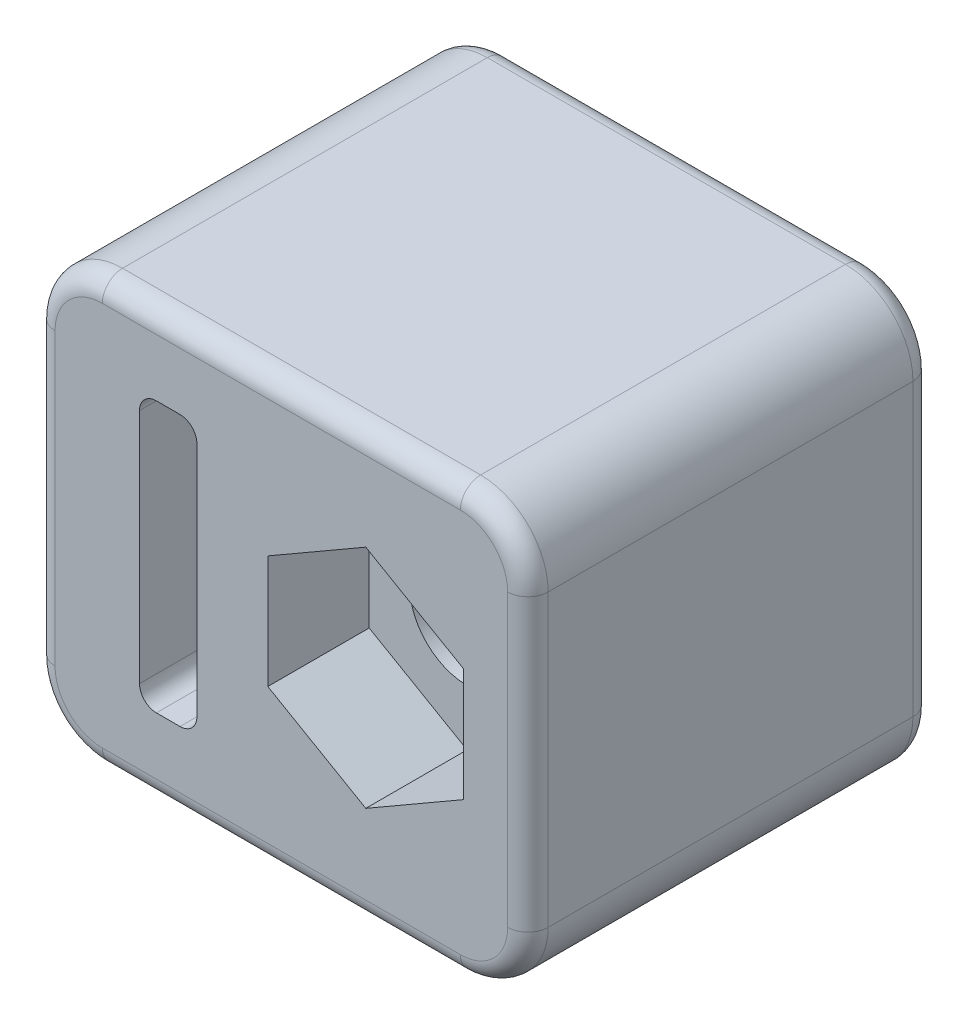
SolidWorks part; units mm, degrees
ref_plane "Front Plane" through (0, 0, 0) normal (0, 0, 1) x (1, 0, 0)
ref_plane "Top Plane" through (0, 0, 0) normal (0, 1, 0) x (1, 0, 0)
ref_plane "Right Plane" through (0, 0, 0) normal (1, 0, 0) x (0, 0, -1)
sketch "Sketch1" plane through (0, 0, 0) normal (0, 0, 1) x (1, 0, 0)
  line L8 (3.1, 9.8) -> (3.1, 2.8)
  line L9 (3.6, 2.3) -> (4.3, 2.3)
  line L10 (4.8, 2.8) -> (4.8, 9.8)
  line L15 (3.6, 10.3) -> (4.3, 10.3)
  line L18 (2, 0) -> (12.6, 0)
  line L19 (0, 2) -> (0, 10.6)
  line L20 (2, 12.6) -> (12.6, 12.6)
  line L21 (14.6, 2) -> (14.6, 10.6)
  arc A13 (3.6, 10.3) -> (3.1, 9.8) centre (3.6, 9.8) ccw
  arc A14 (4.3, 10.3) -> (4.8, 9.8) centre (4.3, 9.8) cw
  arc A15 (3.1, 2.8) -> (3.6, 2.3) centre (3.6, 2.8) ccw
  arc A16 (4.8, 2.8) -> (4.3, 2.3) centre (4.3, 2.8) cw
  circle A17 centre (9.8, 6.3) radius 1.7
  arc A18 (12.6, 12.6) -> (14.6, 10.6) centre (12.6, 10.6) cw
  arc A19 (12.6, 0) -> (14.6, 2) centre (12.6, 2) ccw
  arc A20 (2, 0) -> (0, 2) centre (2, 2) cw
  arc A21 (0, 10.6) -> (2, 12.6) centre (2, 10.6) cw
extrude "Boss-Extrude1" add sketch "Sketch1" along normal blind 12
sketch "Sketch2" plane through (0, 0, 12) normal (0, 0, 1) x (1, 0, 0)
  line L1 (9.8, 9.6486) -> (6.9, 7.9743)
  line L2 (6.9, 7.9743) -> (6.9, 4.6257)
  line L3 (6.9, 4.6257) -> (9.8, 2.9514)
  line L4 (9.8, 2.9514) -> (12.7, 4.6257)
  line L5 (12.7, 4.6257) -> (12.7, 7.9743)
  line L6 (12.7, 7.9743) -> (9.8, 9.6486)
  circle A0 centre (9.8, 6.3) radius 2.9 construction
extrude "Cut-Extrude1" cut sketch "Sketch2" against normal blind 3
sketch "Sketch3" plane through (0, 0, 0) normal (0, 0, -1) x (-1, 0, 0)
  line L0 (-4.8, 9.8) -> (-4.8, 2.8)
  line L1 (-4.3, 2.3) -> (-2.8, 2.3)
  line L2 (-2.3, 2.8) -> (-2.3, 9.8)
  line L3 (-2.8, 10.3) -> (-4.3, 10.3)
  arc A0 (-4.8, 9.8) -> (-4.3, 10.3) centre (-4.3, 9.8) cw
  arc A1 (-2.8, 10.3) -> (-2.3, 9.8) centre (-2.8, 9.8) cw
  arc A2 (-4.8, 2.8) -> (-4.3, 2.3) centre (-4.3, 2.8) ccw
  arc A3 (-2.3, 2.8) -> (-2.8, 2.3) centre (-2.8, 2.8) cw
extrude "Cut-Extrude2" cut sketch "Sketch3" against normal blind 6
fillet "Fillet1" radius 0.6 16 edges at (14.0142, 12.0142, 0) (14.6, 6.3, 0) (14.0142, 0.5858, 0) (7.3, 0, 0) (0.5858, 0.5858, 0) (0, 6.3, 0) (0.5858, 12.0142, 0) (14.0142, 12.0142, 12) (14.6, 6.3, 12) (14.0142, 0.5858, 12) (7.3, 0, 12) (0.5858, 0.5858, 12) (0, 6.3, 12) (0.5858, 12.0142, 12) (7.3, 12.6, 0) (7.3, 12.6, 12)
